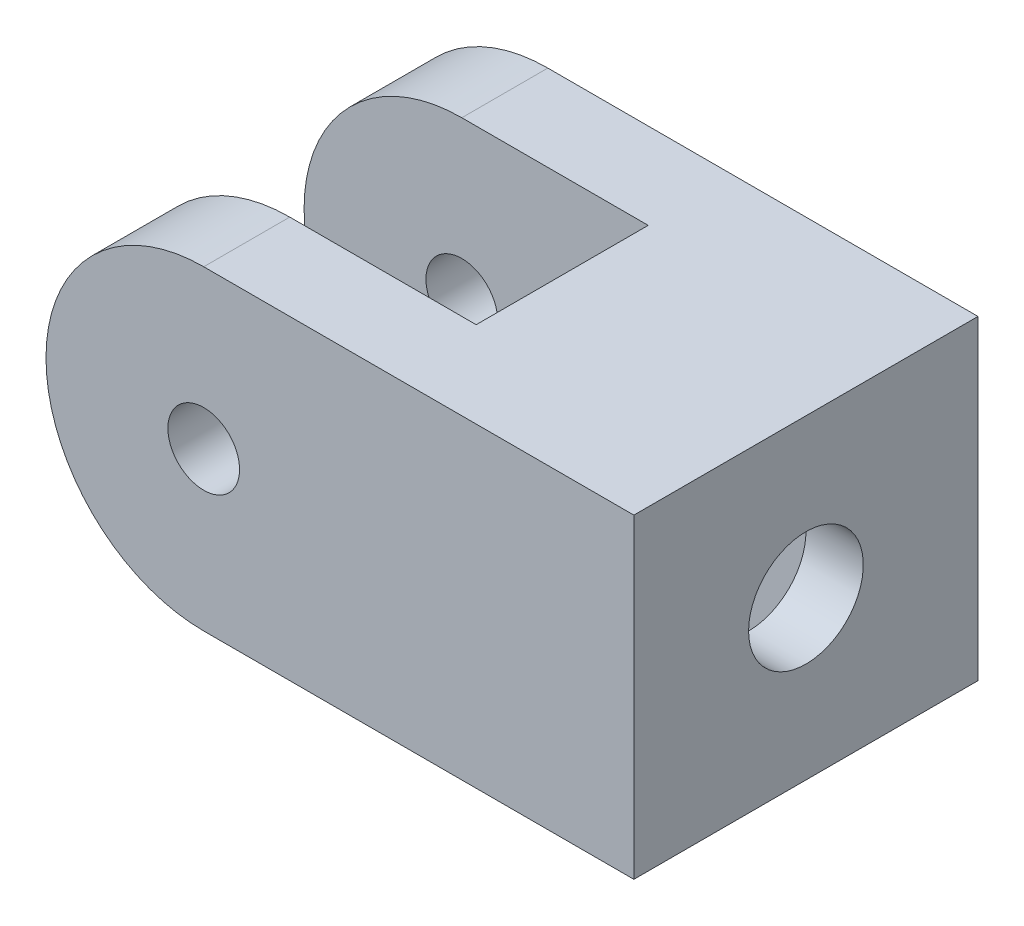
SolidWorks part; units mm, degrees
ref_plane "Front Plane" through (0, 0, 0) normal (0, 0, 1) x (1, 0, 0)
ref_plane "Top Plane" through (0, 0, 0) normal (0, 1, 0) x (1, 0, 0)
ref_plane "Right Plane" through (0, 0, 0) normal (1, 0, 0) x (0, 0, -1)
ref_plane "Plane1" through (0, 0, -24) normal (0, 0, -1) x (-1, 0, 0)
sketch "Sketch1" plane through (0, 0, -24) normal (0, 0, -1) x (-1, 0, 0)
  line L0 (0, 11) -> (-30, 11)
  line L1 (-30, 11) -> (-30, -11)
  line L2 (-30, -11) -> (0, -11)
  arc A0 (0, -11) -> (0, 11) centre (0, 0) ccw
extrude "Boss-Extrude1" add sketch "Sketch1" against normal blind 24
sketch "Sketch2" plane through (0, 11, 0) normal (0, 1, 0) x (-1, 0, 0)
  line L0 (17.1108, -18) -> (17.1108, -6)
  line L1 (17.1108, -6) -> (-13, -6)
  line L2 (-13, -6) -> (-13, -18)
  line L3 (-13, -18) -> (17.1108, -18)
  line L4 (-35.3701, -12) -> (15.4323, -12) construction
  dimension "D1" = 12
  dimension "D2" = 30.1108
extrude "Cut-Extrude1" cut sketch "Sketch2" against normal through all
ref_plane "Plane2" through (19.2, 0, 0) normal (-1, 0, 0) x (0, -1, 0)
sketch "Sketch3" plane through (19.2, 0, 0) normal (-1, 0, 0) x (0, -1, 0)
  line L0 (11, -18.5) -> (11, -5.5)
  line L1 (11, -5.5) -> (-3.7528, -5.5)
  line L2 (-3.7528, -5.5) -> (-7.5056, -12)
  line L3 (-7.5056, -12) -> (-3.7528, -18.5)
  line L4 (-3.7528, -18.5) -> (11, -18.5)
extrude "Cut-Extrude2" cut sketch "Sketch3" against normal blind 6.8
hole_wizard "Ø7.8 (8) Diameter Hole1" positions "Sketch5" profile "Sketch4" hole size "Ø7.8" standard "ANSI Metric"
sketch "Sketch5" plane through (13, 0, 0) normal (-1, 0, 0) x (0, 0, 1)
  point P0 (-12, 0)
sketch "Sketch4" plane through (13, 0, -12) normal (0, 1, 0) x (0, 0, 1)
  line L0 (0, 0) -> (0, 6.2)
  line L1 (0, 6.2) -> (4, 6.2)
  line L2 (4, 6.2) -> (4, 0)
  line L5 (4, 0) -> (0, 0)
  line L11 (0, -6.35) -> (0, 107.95) construction
  dimension "Thru Hole Dia." = 8
  dimension "Thru Hole Depth" = 6.2
hole_wizard "Ø7.8 (8) Diameter Hole2" positions "Sketch7" profile "Sketch6" hole size "Ø7.8" standard "ANSI Metric" end condition through all
sketch "Sketch7" plane through (26, 0, 0) normal (-1, 0, 0) x (0, 0, 1)
  point P0 (-12, 0)
sketch "Sketch6" plane through (26, 0, -12) normal (0, 1, 0) x (0, 0, 1)
  line L0 (0, 0) -> (0, 4)
  line L1 (0, 4) -> (4, 4)
  line L2 (4, 4) -> (4, 0)
  line L5 (4, 0) -> (0, 0)
  line L11 (0, -6.35) -> (0, 107.95) construction
  dimension "Thru Hole Dia." = 8
  dimension "Thru Hole Depth" = 4
hole_wizard "Ø4.7 (5) Diameter Hole2" positions "Sketch9" profile "Sketch8" hole size "Ø4.7" standard "ANSI Metric"
sketch "Sketch9" plane through (0, 0, -24) normal (0, 0, -1) x (-1, 0, 0)
  point P0 (0, 0)
sketch "Sketch8" plane through (0, 0, -24) normal (1, 0, 0) x (0, 1, 0)
  line L0 (0, 0) -> (0, 6)
  line L1 (0, 6) -> (2.5, 6)
  line L2 (2.5, 6) -> (2.5, 0)
  line L5 (2.5, 0) -> (0, 0)
  line L11 (0, -6.35) -> (0, 107.95) construction
  dimension "Thru Hole Dia." = 5
  dimension "Thru Hole Depth" = 6
hole_wizard "Ø4.7 (5) Diameter Hole1" positions "Sketch11" profile "Sketch10" hole size "Ø4.7" standard "ANSI Metric" end condition through all
sketch "Sketch11" plane through (0, 0, -6) normal (0, 0, -1) x (-1, 0, 0)
  point P0 (0, 0)
sketch "Sketch10" plane through (0, 0, -6) normal (1, 0, 0) x (0, 1, 0)
  line L0 (0, 0) -> (0, 6)
  line L1 (0, 6) -> (2.5, 6)
  line L2 (2.5, 6) -> (2.5, 0)
  line L5 (2.5, 0) -> (0, 0)
  line L11 (0, -6.35) -> (0, 107.95) construction
  dimension "Thru Hole Dia." = 5
  dimension "Thru Hole Depth" = 6
